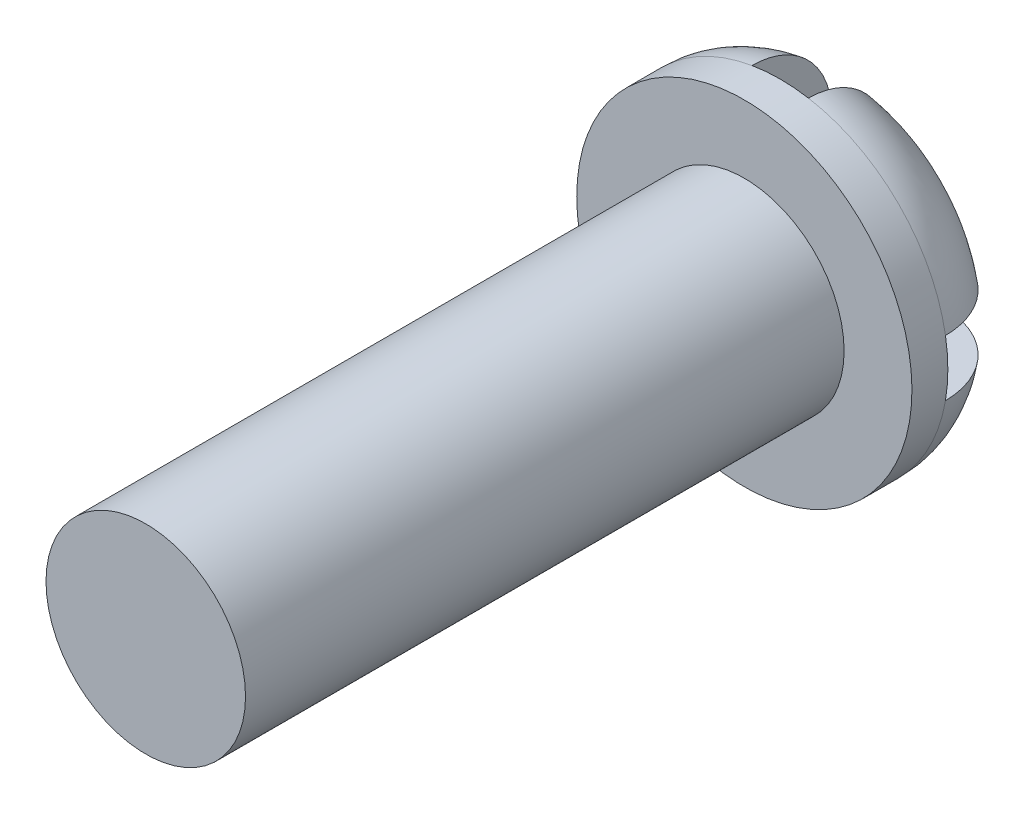
SolidWorks part; units mm, degrees
ref_plane "前视基准面" through (0, 0, 0) normal (0, 0, 1) x (1, 0, 0)
ref_plane "上视基准面" through (0, 0, 0) normal (0, 1, 0) x (1, 0, 0)
ref_plane "右视基准面" through (0, 0, 0) normal (1, 0, 0) x (0, 0, -1)
sketch "草图1" plane through (0, 0, 0) normal (0, 0, 1) x (1, 0, 0)
  circle A0 centre (0, 0) radius 2.5
  dimension "D1" = 5
extrude "凸台-拉伸1" add sketch "草图1" along normal blind 15
sketch "草图2" plane through (0, 0, 0) normal (0, 0, -1) x (-1, 0, 0)
  circle A0 centre (0, 0) radius 4.2
  dimension "D1" = 8.4
extrude "凸台-拉伸2" add sketch "草图2" along normal blind 2.9
fillet "圆角1" radius 2 1 edges at (-4.2, 0, -2.9)
sketch "草图3" plane through (0, 0, -2.9) normal (0, 0, -1) x (-1, 0, 0)
  line L0 (-0.7071, 0.7071) -> (-0.7071, 6.0064)
  line L1 (1, -1) -> (-1, -1) construction
  line L2 (1, -1) -> (1, 1) construction
  line L3 (1, 1) -> (-1, 1) construction
  line L4 (-1, -1) -> (-1, 1) construction
  line L5 (1, -1) -> (-1, 1) construction
  line L6 (1, 1) -> (-1, -1) construction
  line L7 (0.7071, 0.7071) -> (0.7071, 6.0064)
  line L8 (0.7071, 6.0064) -> (-0.7071, 6.0064)
  line L9 (0.7071, 0.7071) -> (6.0064, 0.7071)
  line L10 (0.7071, -0.7071) -> (6.0064, -0.7071)
  line L11 (6.0064, -0.7071) -> (6.0064, 0.7071)
  line L12 (0.7071, -0.7071) -> (0.7071, -6.0064)
  line L13 (-0.7071, -0.7071) -> (-0.7071, -6.0064)
  line L14 (-0.7071, -6.0064) -> (0.7071, -6.0064)
  line L15 (-0.7071, -0.7071) -> (-6.0064, -0.7071)
  line L16 (-0.7071, 0.7071) -> (-6.0064, 0.7071)
  line L17 (-6.0064, 0.7071) -> (-6.0064, -0.7071)
  circle A0 centre (0, 0) radius 1 construction
  dimension "D1" = 4
extrude "切除-拉伸1" cut sketch "草图3" against normal blind 2
